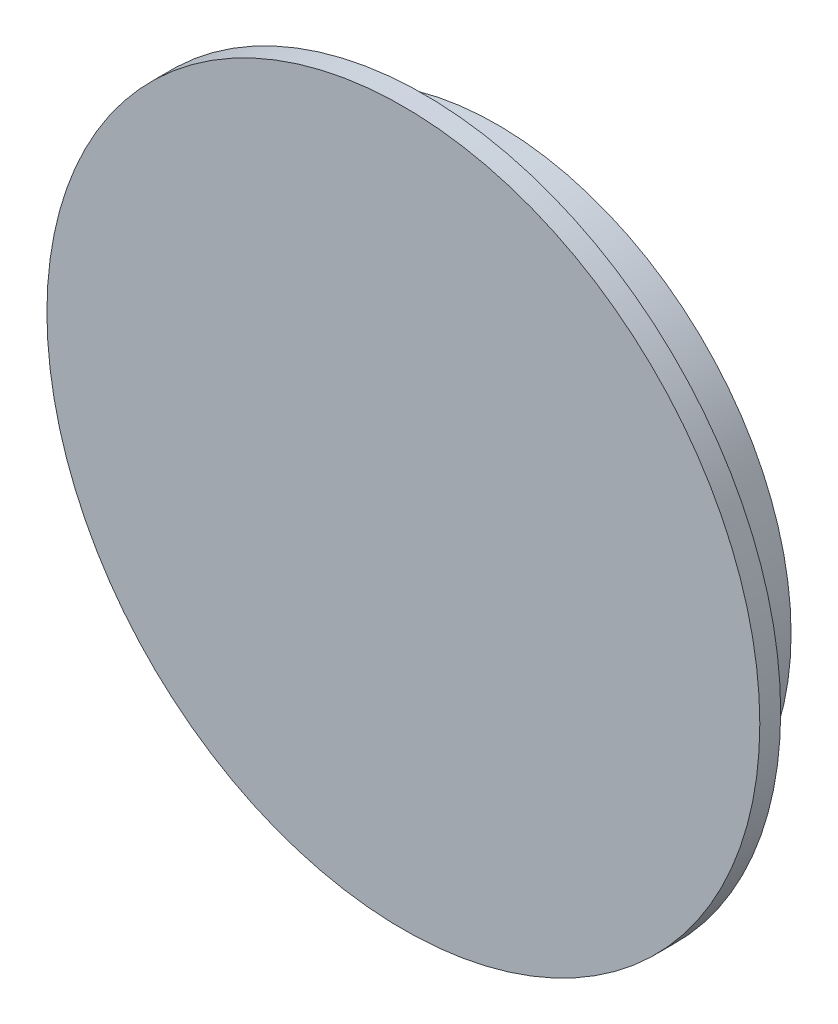
SolidWorks part; units mm, degrees
material "Custom Plastic"
ref_plane "X-Y Datum" through (0, 0, 0) normal (0, 0, 1) x (1, 0, 0)
ref_plane "X-Z Datum" through (0, 0, 0) normal (0, 1, 0) x (1, 0, 0)
ref_plane "Y-Z Datum" through (0, 0, 0) normal (1, 0, 0) x (0, 0, -1)
sketch "Sketch1" plane through (0, 0, 0) normal (0, 0, 1) x (1, 0, 0)
  circle A0 centre (0, 0) radius 14.1
  circle A1 centre (0, 0) radius 12.6
  circle A2 centre (0, 0) radius 17.1
  dimension "D1" = 28.2
  dimension "D2" = 1.5
  dimension "D3" = 3
extrude "Boss-Extrude1" add sketch "Sketch1" along normal blind 3.5 contours A0 A1
sketch "Sketch2" plane through (0, 0, 3.5) normal (0, 0, 1) x (1, 0, 0)
  circle A1 centre (0, 0) radius 17.1
  circle A2 centre (0, 0) radius 17.1
  circle A3 centre (0, 0) radius 12.6
  circle A4 centre (0, 0) radius 12.6
  circle A5 centre (0, 0) radius 14.1
  circle A6 centre (0, 0) radius 14.1
  circle M4 centre (0, 0) radius 12.6
  circle M5 centre (0, 0) radius 14.1
  dimension "D1" = 0
  dimension "D2" = 0
  dimension "D3" = 0
extrude "Boss-Extrude2" add sketch "Sketch2" along normal blind 1 contours M4 | M5 M4 | A2 M5
